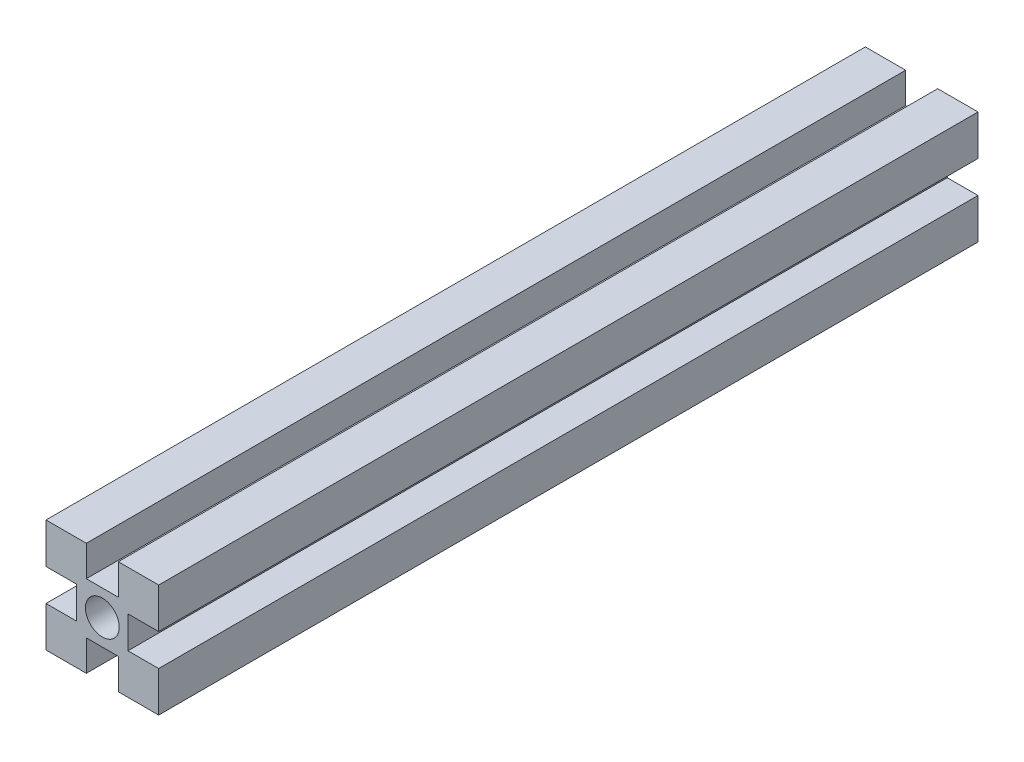
SolidWorks part; units mm, degrees
ref_plane "Front Plane" through (0, 0, 0) normal (0, 0, 1) x (1, 0, 0)
ref_plane "Top Plane" through (0, 0, 0) normal (0, 1, 0) x (1, 0, 0)
ref_plane "Right Plane" through (0, 0, 0) normal (1, 0, 0) x (0, 0, -1)
sketch "Esquisse1" plane through (0, 0, 0) normal (0, 0, 1) x (1, 0, 0)
  line L0 (3.125, 11) -> (11, 11)
  line L1 (-11, -11) -> (-3.125, -11)
  line L2 (-11, -11) -> (-11, -3.125)
  line L3 (-11, 11) -> (-3.125, 11)
  line L4 (11, -11) -> (11, -3.125)
  line L5 (-11, -11) -> (11, 11) construction
  line L6 (-11, 11) -> (11, -11) construction
  line L7 (11, 3.125) -> (5, 3.125)
  line L9 (11, -3.125) -> (5, -3.125)
  line L10 (5, 3.125) -> (5, -3.125)
  line L11 (-11, 3.125) -> (-5, 3.125)
  line L13 (-11, -3.125) -> (-5, -3.125)
  line L14 (-5, 3.125) -> (-5, -3.125)
  line L16 (-3.125, 11) -> (-3.125, 5)
  line L17 (-3.125, 5) -> (3.125, 5)
  line L18 (3.125, 11) -> (3.125, 5)
  line L20 (-3.125, -11) -> (-3.125, -5)
  line L21 (-3.125, -5) -> (3.125, -5)
  line L22 (3.125, -11) -> (3.125, -5)
  line L23 (11, 3.125) -> (11, 11)
  line L24 (3.125, -11) -> (11, -11)
  line L25 (-11, 3.125) -> (-11, 11)
  line L26 (0, 5) -> (0, -5) construction
  line L27 (-5, 0) -> (5, 0) construction
  point P0 (0, 0)
  dimension "D1" = 22
  dimension "D2" = 6.25
  dimension "D3" = 6
extrude "Boss.-Extru.1" add sketch "Esquisse1" along normal blind 160
hole_wizard "Dégagement M61" positions "Esquisse2" profile "Esquisse3" hole size "M6" standard "ISO"
sketch "Esquisse2" plane through (0, 0, 160) normal (0, 0, 1) x (1, 0, 0)
  point P0 (0, 0)
sketch "Esquisse3" plane through (0, 0, 160) normal (1, 0, 0) x (0, -1, 0)
  line L0 (0, 0) -> (0, 25)
  line L1 (0, 25) -> (3.3, 23.0172)
  line L2 (3.3, 23.0172) -> (3.3, 0)
  line L5 (3.3, 0) -> (0, 0)
  line L10 (0, 25) -> (-3.3, 23.0172) construction
  line L11 (0, -6.35) -> (0, 107.95) construction
  dimension "Diamètre du perçage" = 6.6
  dimension "Profondeur du perçage" = 25
  dimension "Angle de pointe" = 118
ref_plane "Plan1" through (0, 0, 80) normal (0, 0, 1) x (1, 0, 0)
mirror "Symétrie1" about plane through (0, 0, 80) normal (0, 0, 1) of "Dégagement M61"
